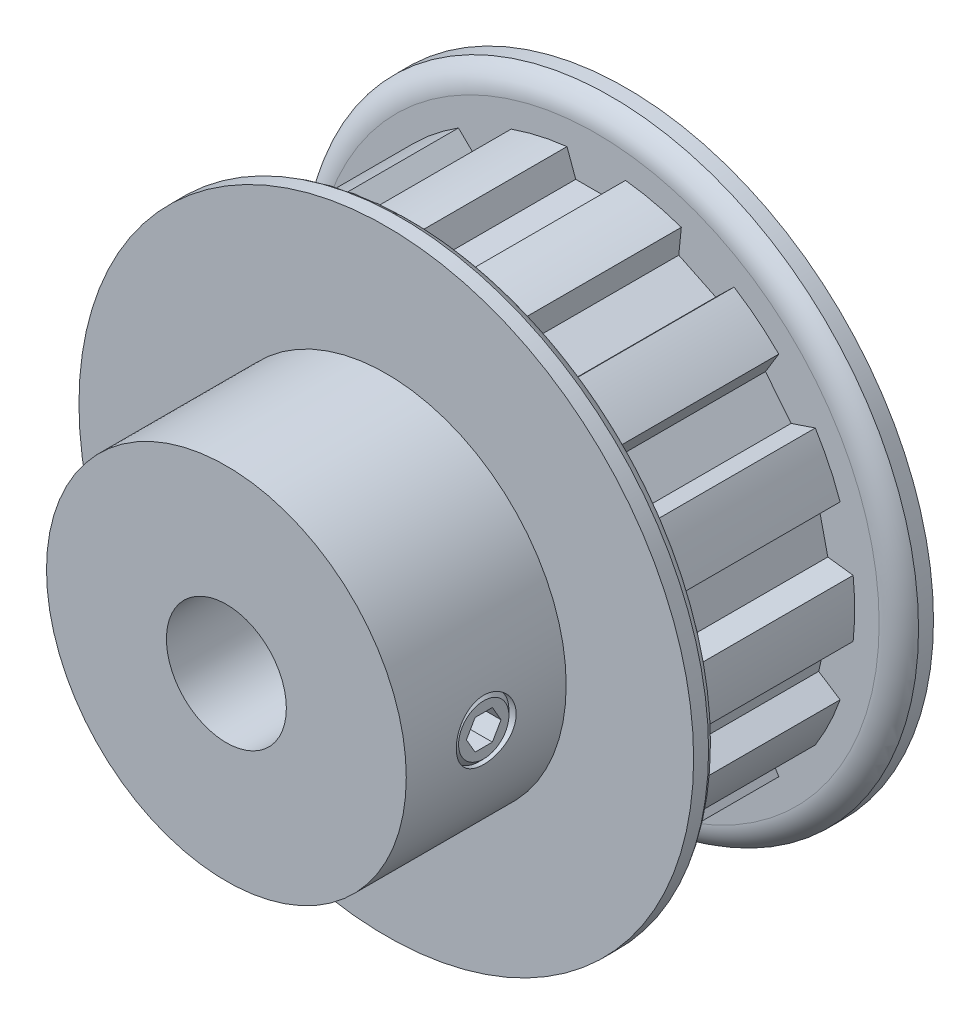
SolidWorks part; units mm, degrees
ref_plane "Front Plane" through (0, 0, 0) normal (0, 0, 1) x (1, 0, 0)
ref_plane "Top Plane" through (0, 0, 0) normal (0, 1, 0) x (1, 0, 0)
ref_plane "Right Plane" through (0, 0, 0) normal (1, 0, 0) x (0, 0, -1)
sketch "Sketch1" plane through (0, 0, 0) normal (0, 0, 1) x (1, 0, 0)
  line L0 (-2.3241, 20.3962) -> (-1.6307, 18.4912)
  line L1 (-1.6307, 18.4912) -> (1.6307, 18.4912)
  line L2 (1.6307, 18.4912) -> (2.3241, 20.3962)
  line L3 (-2.3241, 20.3962) -> (2.3241, 20.3962)
  line L4 (0, 0) -> (0, 18.4912) construction
  line L5 (0, 18.4912) -> (0, 22.0472) construction
  circle A0 centre (0, 0) radius 21.2217 construction
  circle A1 centre (0, 0) radius 24.4094 construction
  circle A2 centre (0, 0) radius 20.5282 construction
  point P6 (0, 20.3962)
  point P11 (0, 21.2217)
  point P13 (0, 24.4094)
  point P14 (0, 20.5282)
  dimension "D1" = 1.651
  dimension "D2" = 0.8255
sketch "Sketch2" plane through (0, 0, 0) normal (1, 0, 0) x (0, 0, -1)
  line L0 (-15.875, 4.7625) -> (15.875, 4.7625)
  line L1 (-15.875, 4.7625) -> (-15.875, 14.2875)
  line L2 (-15.875, 14.2875) -> (-3.175, 14.2875)
  line L3 (-3.175, 14.2875) -> (-3.175, 24.4094)
  line L4 (-3.175, 24.4094) -> (-0.8001, 24.4094) construction
  line L5 (-0.8001, 24.4094) -> (-0.8001, 20.5282) construction
  line L6 (-0.8001, 20.5282) -> (13.5001, 20.5282)
  line L7 (13.5001, 20.5282) -> (13.5001, 24.4094) construction
  line L8 (13.5001, 24.4094) -> (15.875, 24.4094) construction
  line L9 (15.875, 24.4094) -> (15.875, 4.7625)
  line L10 (-15.875, 0) -> (15.875, 0) construction
  line L13 (-3.175, 24.4094) -> (-1.9876, 24.4094)
  line L14 (-0.8001, 22.4688) -> (-0.8001, 20.5282)
  line L15 (13.5001, 20.5282) -> (13.5001, 22.4688)
  line L16 (14.6875, 24.4094) -> (15.875, 24.4094)
  arc A0 (-0.8001, 22.4688) -> (-1.9876, 24.4094) centre (-2.9796, 22.4688) ccw
  arc A1 (13.5001, 22.4688) -> (14.6875, 24.4094) centre (15.6796, 22.4688) cw
  point P12 (-0.8001, 22.4688)
  point P14 (-1.9876, 24.4094)
  point P20 (13.5001, 22.4688)
  point P21 (14.6875, 24.4094)
  point P25 (13.5001, 0)
  point P26 (-0.8001, 0)
  dimension "Bore" = 9.525
  dimension "Hub Dia" = 28.575
  dimension "Outside Width" = 19.05
  dimension "Inside Width" = 14.3002
revolve "Revolve1" add sketch "Sketch2" angle 360 mid plane about L10
sketch "Sketch3" plane through (0, 0, 0) normal (0, 0, 1) x (1, 0, 0)
  line L0 (-1.6307, 18.4912) -> (1.6307, 18.4912) construction
  line L1 (1.6307, 18.4912) -> (2.3241, 20.3962) construction
  line L2 (-2.3241, 20.3962) -> (-1.6307, 18.4912) construction
  line L3 (-1.6307, 18.4912) -> (1.6307, 18.4912)
  line L4 (1.6307, 18.4912) -> (2.3241, 20.3962)
  line L5 (-2.3241, 20.3962) -> (-1.6307, 18.4912)
  circle A0 centre (0, 0) radius 20.5282 construction
  arc A1 (2.3241, 20.3962) -> (-2.3241, 20.3962) centre (0, 0) ccw
extrude "Cut-Extrude1" cut sketch "Sketch3" against normal up to vertex (13.5001 mm away) from vertex at 0.8001 starting at point (0, 20.5282, 0.8001)
pattern_circular "CirPattern1" count 14 over 360 about axis through (0, 0, 0) along (0, 0, 1) of "Cut-Extrude1"
sketch "Sketch4" plane through (0, 0, 0) normal (1, 0, 0) x (0, -1, 0)
  line L0 (0, -3.175) -> (0, -15.875) construction
  line L1 (-14.2875, -3.175) -> (14.2875, -3.175) construction
  line L2 (-14.2875, -15.875) -> (14.2875, -15.875) construction
  circle A0 centre (0, -9.525) radius 2.3813
  dimension "D1" = 4.7625
extrude "Cut-Extrude2" cut sketch "Sketch4" along normal through all
ref_plane "Plane1" through (0, 0, 9.525) normal (0, 0, 1) x (1, 0, 0)
sketch "Sketch5" plane through (0, 0, 9.525) normal (0, 0, 1) x (1, 0, 0)
  line L0 (0, 0.1664) -> (0, 14.2875) construction
  line L1 (4.7625, -2.0003) -> (4.7625, 0)
  line L2 (5.1435, -2.3813) -> (13.7067, -2.3813)
  line L3 (4.7625, 0) -> (14.2875, 0) construction
  line L4 (4.7625, 0) -> (14.0877, 0)
  line L5 (14.0877, 0) -> (14.0877, -2.0003)
  line L6 (5.1435, -2.3813) -> (4.7625, -2.0003)
  line L7 (14.0877, -2.0003) -> (13.7067, -2.3813)
  circle A0 centre (0, 0) radius 14.2875 construction
  circle A1 centre (0, 0) radius 4.7625 construction
  point P2 (4.7625, -2.3813)
  point P11 (14.0877, -2.3813)
revolve "Revolve2" add sketch "Sketch5" angle 360 mid plane about L4
sketch "Sketch6" plane through (14.0877, 5.3841, 0) normal (-1, 0, 0) x (0, -1, 0)
  line L1 (5.3841, 10.8998) -> (4.1935, 10.2124)
  line L2 (4.1935, 10.2124) -> (4.1935, 8.8376)
  line L3 (4.1935, 8.8376) -> (5.3841, 8.1502)
  line L4 (5.3841, 8.1502) -> (6.5748, 8.8376)
  line L5 (6.5748, 8.8376) -> (6.5748, 10.2124)
  line L6 (6.5748, 10.2124) -> (5.3841, 10.8998)
  circle A0 centre (5.3841, 9.525) radius 1.1906 construction
  dimension "D1" = 2.3813
extrude "Cut-Extrude3" cut sketch "Sketch6" along normal blind 1.7859
equation "\"D2@Sketch1\" = \"D1@Sketch1\"/2"
equation "\"D1@Sketch4\" = \"Bore@Sketch2\"/2"
equation "\"D1@Sketch6\" = \"D1@Sketch4\"/2"
equation "\"D1@Cut-Extrude3\" = \"D1@Sketch6\"*.75"
